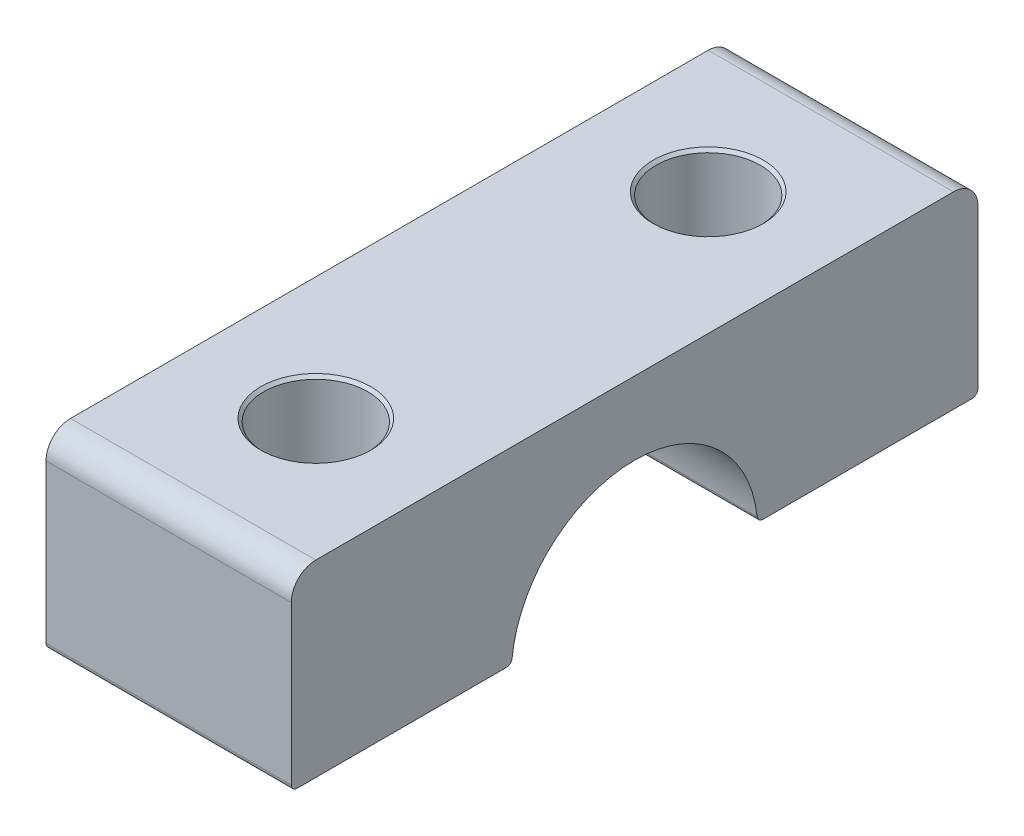
SolidWorks part; units mm, degrees
ref_plane "front" through (0, 0, 0) normal (0, 0, 1) x (1, 0, 0)
ref_plane "top" through (0, 0, 0) normal (0, 1, 0) x (1, 0, 0)
ref_plane "right" through (0, 0, 0) normal (1, 0, 0) x (0, 0, -1)
sketch "Sketch1" plane through (0, 0, 0) normal (1, 0, 0) x (0, 0, -1)
  line L0 (16.6184, 1.016) -> (43.688, 1.016)
  line L1 (-41.275, 25.4) -> (41.275, 25.4)
  line L2 (-44.45, 22.225) -> (-44.45, 1.778)
  line L3 (-43.688, 1.016) -> (-16.6184, 1.016)
  line L4 (44.45, 22.225) -> (44.45, 1.778)
  line L5 (0, 0) -> (0, -34.244) construction
  arc A0 (15.8607, 1.6969) -> (-15.8607, 1.6969) centre (0, 0) ccw
  arc A1 (41.275, 25.4) -> (44.45, 22.225) centre (41.275, 22.225) cw
  arc A2 (-41.275, 25.4) -> (-44.45, 22.225) centre (-41.275, 22.225) ccw
  arc A3 (43.688, 1.016) -> (44.45, 1.778) centre (43.688, 1.778) ccw
  arc A4 (16.6184, 1.016) -> (15.8607, 1.6969) centre (16.6184, 1.778) cw
  arc A5 (-16.6184, 1.016) -> (-15.8607, 1.6969) centre (-16.6184, 1.778) ccw
  arc A6 (-44.45, 1.778) -> (-43.688, 1.016) centre (-43.688, 1.778) ccw
  point P15 (44.45, 1.016)
  point P22 (-44.45, 1.016)
  dimension "D4" = 15.9512
  dimension "D5" = 3.175
  dimension "D6" = 0.762
  dimension "D1" = 88.9
  dimension "D2" = 1.016
  dimension "D3" = 25.4
extrude "Base-Extrude" add sketch "Sketch1" along normal mid plane 31.75
sketch "Sketch2" plane through (0, 25.4, 0) normal (0, 1, 0) x (-1, 0, 0)
  circle A0 centre (0, 25.4) radius 6.7469
  circle A1 centre (0, -25.4) radius 6.7469
  circle A2 centre (0, -25.4) radius 13.4938 construction
  circle A3 centre (0, 25.4) radius 13.4938 construction
  dimension "D3" = 26.9875
  dimension "D4" = 13.4937
  dimension "D1" = 25.4
  dimension "D2" = 25.4
extrude "Cut-Extrude1" cut sketch "Sketch2" against normal through all
chamfer "Chamfer1" distance 0.381 angle 45 4 edges at (0, 1.016, 32.1469) (0, 25.4, 32.1469) (0, 1.016, -18.6531) (0, 25.4, -18.6531)
